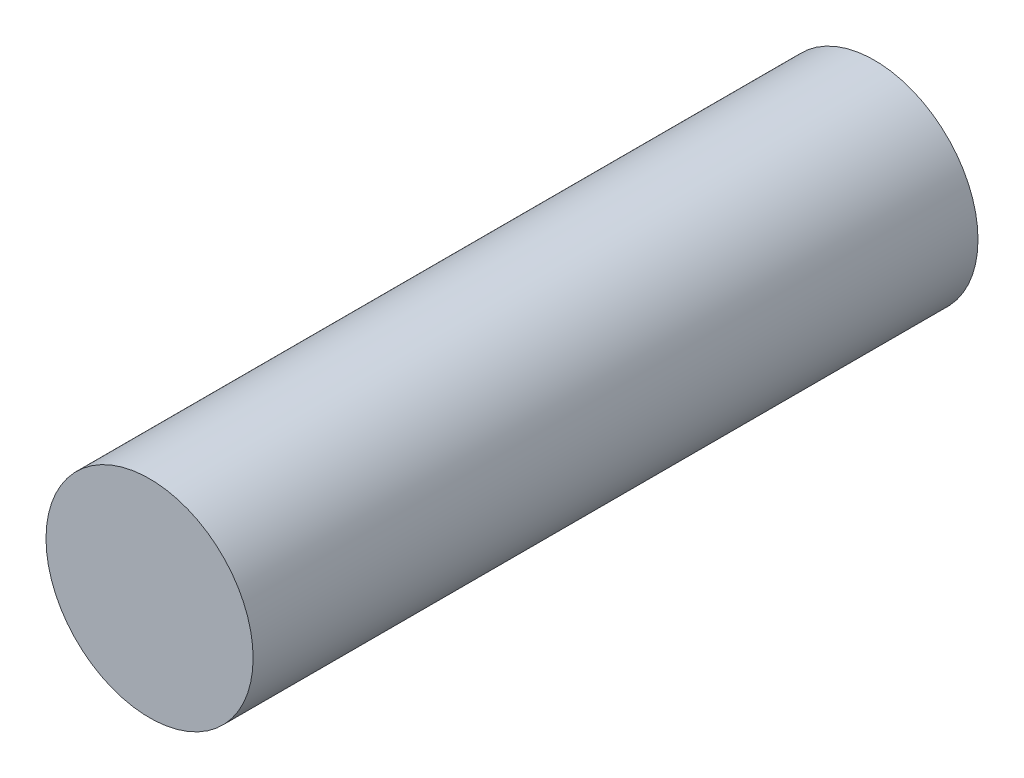
SolidWorks part; units mm, degrees
ref_plane "Front Plane" through (0, 0, 0) normal (0, 0, 1) x (1, 0, 0)
ref_plane "Top Plane" through (0, 0, 0) normal (0, 1, 0) x (1, 0, 0)
ref_plane "Right Plane" through (0, 0, 0) normal (1, 0, 0) x (0, 0, -1)
sketch "Sketch1" plane through (0, 0, 0) normal (0, 0, 1) x (1, 0, 0)
  circle A0 centre (0, 0) radius 12.7
  dimension "D1" = 25.4
extrude "Boss-Extrude1" add sketch "Sketch1" along normal blind 88.9 contours A0
